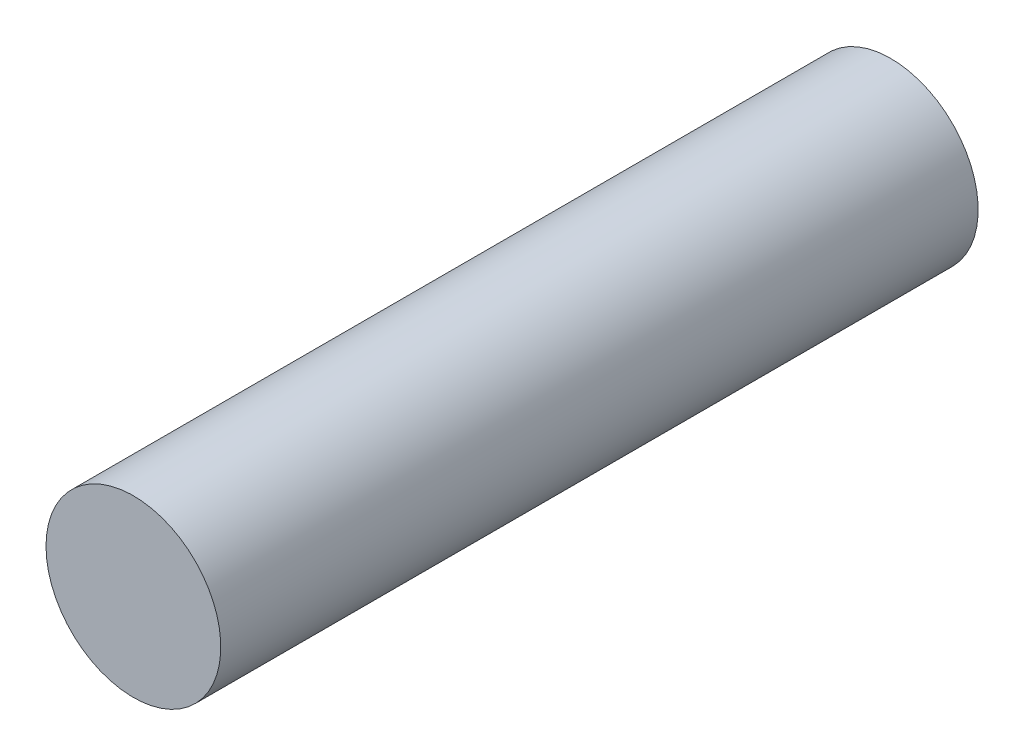
SolidWorks part; units mm, degrees
material "6061 Alloy"
ref_plane "Front Plane" through (0, 0, 0) normal (0, 0, 1) x (1, 0, 0)
ref_plane "Top Plane" through (0, 0, 0) normal (0, 1, 0) x (1, 0, 0)
ref_plane "Right Plane" through (0, 0, 0) normal (1, 0, 0) x (0, 0, -1)
sketch "Sketch1" plane through (0, 0, 0) normal (0, 0, 1) x (1, 0, 0)
  circle A0 centre (0, 0) radius 3
extrude "Boss-Extrude1" add sketch "Sketch1" along normal blind 26
